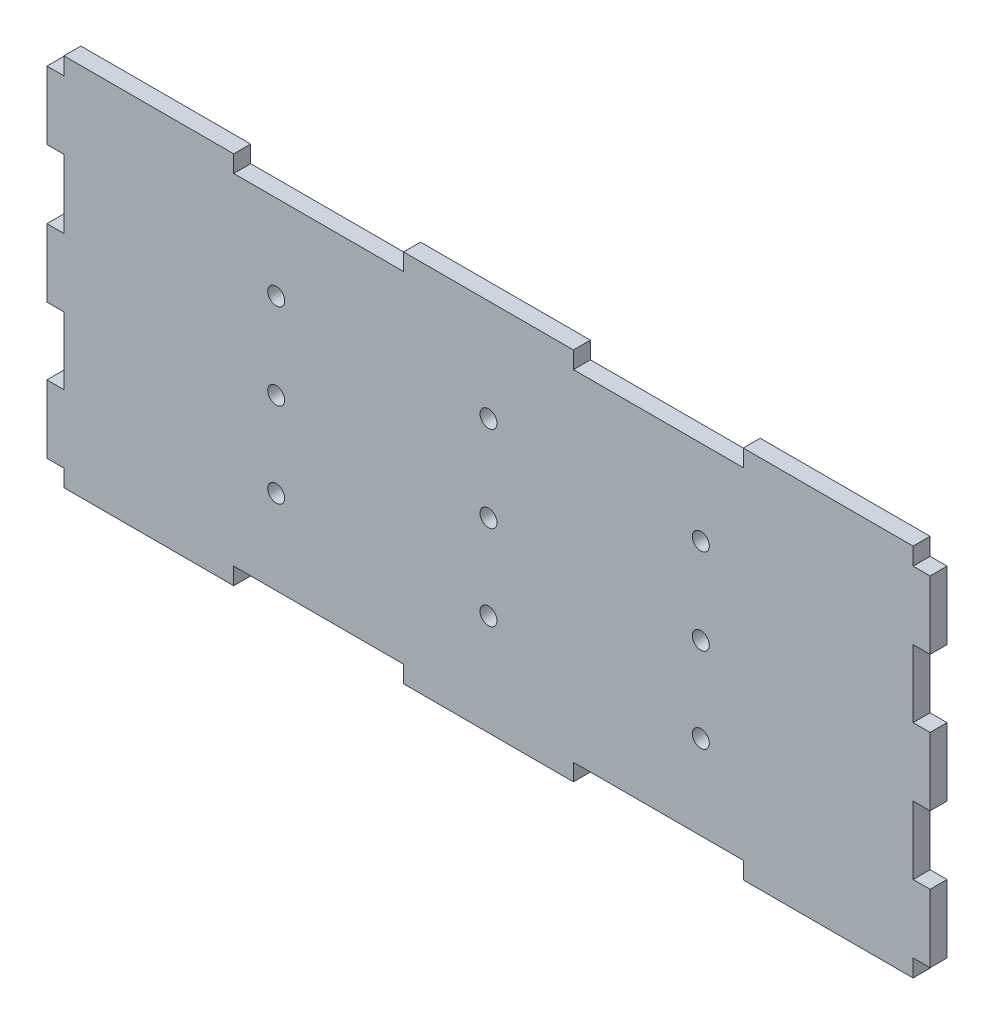
SolidWorks part; units mm, degrees
material "Pinho"
ref_plane "Plano frontal" through (0, 0, 0) normal (0, 0, 1) x (1, 0, 0)
ref_plane "Plano superior" through (0, 0, 0) normal (0, 1, 0) x (1, 0, 0)
ref_plane "Plano direito" through (0, 0, 0) normal (1, 0, 0) x (0, 0, -1)
sketch "Esboço1" plane through (0, 0, 0) normal (0, 0, 1) x (1, 0, 0)
  line L0 (-82.2996, -0.178) -> (73.7004, -0.178) construction
  line L1 (40.7004, -30.0685) -> (10.7004, -30.0685)
  line L2 (70.7004, -18) -> (70.7004, -6)
  line L3 (40.7004, 30) -> (10.7004, 30)
  line L4 (-79.2996, -18.0685) -> (-79.2996, -6.178)
  line L5 (70.7004, 6) -> (70.7004, 17.9315)
  line L6 (-19.2996, 30) -> (-49.2996, 30)
  line L7 (-79.2996, 29.9315) -> (-82.2996, 29.9315)
  line L9 (-79.2996, 17.9315) -> (-82.2996, 17.9315)
  line L10 (-82.2996, 29.9315) -> (-82.2996, 17.9315)
  line L11 (-79.2996, -30.0685) -> (-82.2996, -30.0685)
  line L13 (-79.2996, -18.0685) -> (-82.2996, -18.0685)
  line L14 (-82.2996, -30.0685) -> (-82.2996, -18.0685)
  line L15 (-4.2996, 33) -> (-4.2996, -33.0685) construction
  line L16 (-79.2996, 5.822) -> (-79.2996, 17.9315)
  line L17 (-82.2996, -6.178) -> (-79.2996, -6.178)
  line L18 (-82.2996, -6.178) -> (-82.2996, 5.822)
  line L19 (-82.2996, 5.822) -> (-79.2996, 5.822)
  line L20 (70.7004, -6) -> (73.7004, -6)
  line L22 (70.7004, 6) -> (73.7004, 6)
  line L23 (73.7004, -6) -> (73.7004, 6)
  line L25 (-79.2996, 29.9315) -> (-79.2996, 33)
  line L26 (70.7004, 29.9315) -> (73.7004, 29.9315)
  line L28 (70.7004, 17.9315) -> (73.7004, 17.9315)
  line L29 (73.7004, 29.9315) -> (73.7004, 17.9315)
  line L30 (70.7004, -30) -> (73.7004, -30)
  line L32 (70.7004, -18) -> (73.7004, -18)
  line L33 (73.7004, -30) -> (73.7004, -18)
  line L34 (-79.2996, 33) -> (-49.2996, 33)
  line L35 (-49.2996, 30) -> (-49.2996, 33)
  line L37 (70.7004, 29.9315) -> (70.7004, 33)
  line L38 (70.7004, 33) -> (40.7004, 33)
  line L39 (40.7004, 30) -> (40.7004, 33)
  line L41 (-19.2996, 30) -> (-19.2996, 33)
  line L42 (-19.2996, 33) -> (10.7004, 33)
  line L43 (10.7004, 30) -> (10.7004, 33)
  line L44 (-19.2996, -30.0685) -> (-49.2996, -30.0685)
  line L46 (-19.2996, -30.0685) -> (-19.2996, -33.0685)
  line L47 (-19.2996, -33.0685) -> (10.7004, -33.0685)
  line L48 (10.7004, -30.0685) -> (10.7004, -33.0685)
  line L49 (70.7004, 15) -> (33.2004, 15) construction
  line L50 (33.2004, 15) -> (-4.2996, 15) construction
  line L52 (-79.2996, -30.0685) -> (-79.2996, -33.0685)
  line L53 (-79.2996, -33.0685) -> (-49.2996, -33.0685)
  line L54 (-49.2996, -30.0685) -> (-49.2996, -33.0685)
  line L56 (70.7004, -30) -> (70.7004, -33.0685)
  line L57 (70.7004, -33.0685) -> (40.7004, -33.0685)
  line L58 (40.7004, -30.0685) -> (40.7004, -33.0685)
  line L59 (33.2004, 15) -> (33.2004, -30.0685) construction
  line L60 (-4.2996, 15) -> (-41.7996, 15) construction
  line L61 (70.7004, -15.178) -> (-79.2996, -15.178) construction
  line L62 (-41.7996, 15) -> (-79.2996, 15) construction
  line L63 (-41.7996, 15) -> (-41.7996, -30.0685) construction
  circle A0 centre (33.2004, 15) radius 1.5
  circle A1 centre (-4.2996, -0.178) radius 1.5
  circle A2 centre (-41.7996, 15) radius 1.5
  circle A3 centre (-41.7996, -0.178) radius 1.5
  circle A4 centre (-4.2996, -15.178) radius 1.5
  circle A5 centre (-41.7996, -15.178) radius 1.5
  circle A6 centre (33.2004, -0.178) radius 1.5
  circle A7 centre (33.2004, -15.178) radius 1.5
  circle A8 centre (-4.2996, 15) radius 1.5
  point P0 (0, 0)
  dimension "D28" = 37.5
  dimension "D29" = 37.5
  dimension "D30" = 37.5
  dimension "D33" = 3
  dimension "D1" = 60
  dimension "D2" = 150
  dimension "D3" = 3
  dimension "D4" = 12
  dimension "D5" = 12
  dimension "D6" = 12
  dimension "D7" = 3
  dimension "D8" = 3
  dimension "D9" = 6
  dimension "D10" = 12
  dimension "D11" = 3
  dimension "D12" = 12
  dimension "D13" = 3
  dimension "D14" = 12
  dimension "D15" = 3
  dimension "D16" = 30
  dimension "D17" = 30
  dimension "D18" = 30
  dimension "D19" = 3
  dimension "D20" = 3
  dimension "D21" = 3
  dimension "D22" = 30
  dimension "D23" = 30
  dimension "D24" = 30
  dimension "D25" = 3
  dimension "D26" = 3
  dimension "D27" = 3
  dimension "D31" = 37.5
  dimension "D32" = 15
extrude "Ressalto-extrusão1" add sketch "Esboço1" along normal blind 3
